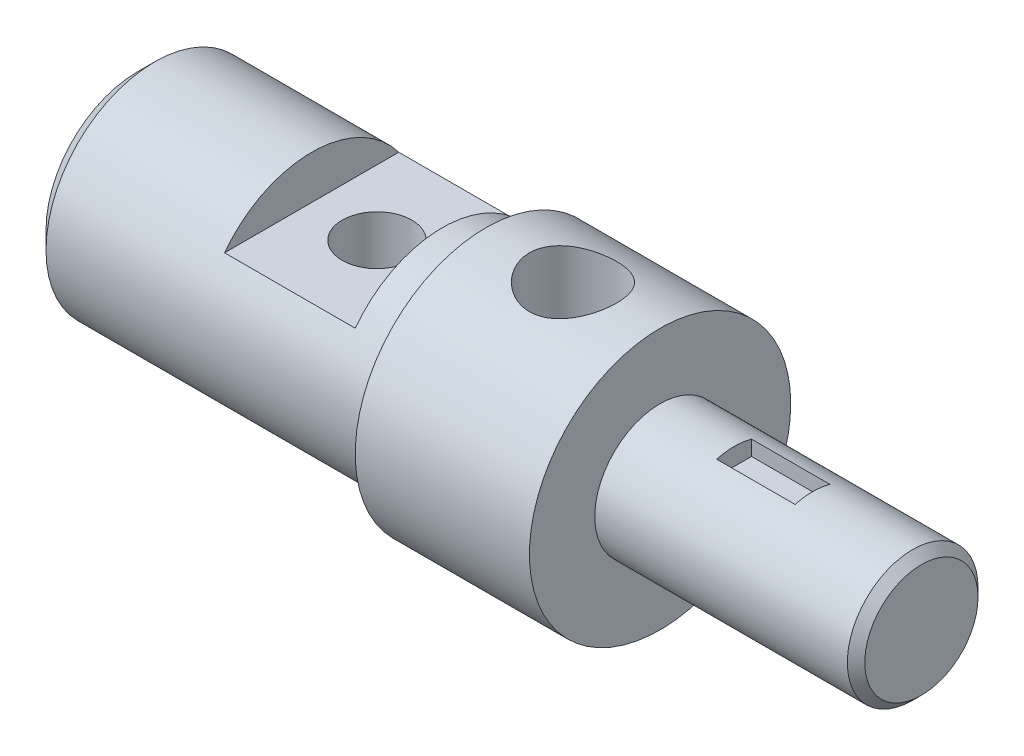
SolidWorks part; units mm, degrees
ref_plane "Спереди" through (0, 0, 0) normal (0, 0, 1) x (1, 0, 0)
ref_plane "Сверху" through (0, 0, 0) normal (0, 1, 0) x (1, 0, 0)
ref_plane "Справа" through (0, 0, 0) normal (1, 0, 0) x (0, 0, -1)
sketch "Эскиз1" plane through (0, 0, 0) normal (0, 0, 1) x (1, 0, 0)
  line L1 (0, 0) -> (0, 25)
  line L2 (0, 25) -> (80, 25)
  line L3 (80, 25) -> (80, 30)
  line L4 (80, 30) -> (120, 30)
  line L5 (120, 30) -> (120, 15)
  line L6 (120, 15) -> (180, 15)
  line L7 (180, 15) -> (180, 0)
  line L8 (0, 0) -> (180, 0)
  line L9 (0, 0) -> (-45.0163, 0) construction
  dimension "D1" = 60
  dimension "D2" = 50
  dimension "D3" = 30
  dimension "D4" = 180
  dimension "D5" = 80
  dimension "D6" = 60
revolve "Повернуть1" add sketch "Эскиз1" angle 360 about L9
sketch "Эскиз10" plane through (0, 0, 0) normal (0, 0, 1) x (1, 0, 0)
  line L0 (80, 25) -> (0, 25) construction
  line L1 (40, 25) -> (70, 25)
  line L2 (40, 25) -> (40, 15)
  line L3 (40, 15) -> (70, 15)
  line L4 (70, 25) -> (70, 15)
  line L5 (0, 25) -> (0, -25) construction
  line L6 (0, -25) -> (80, -25) construction
  dimension "D1" = 40
  dimension "D2" = 30
  dimension "D3" = 40
extrude "Вырез-Вытянуть7" cut sketch "Эскиз10" against normal through all both and the other way through all
ref_plane "Плоскость4" through (0, 30, 0) normal (0, 1, 0) x (1, 0, 0)
sketch "Эскиз14" plane through (0, 15, 0) normal (0, 1, 0) x (1, 0, 0)
  line L0 (40, 0) -> (70, 0) construction
  line L1 (40, -20) -> (40, 20) construction
  line L2 (70, 20) -> (70, -20) construction
  circle A0 centre (55, 0) radius 8
  point P9 (55, 0)
  dimension "D1" = 16
extrude "Вырез-Вытянуть8" cut sketch "Эскиз14" against normal through all
sketch "Эскиз6" plane through (0, 0, 0) normal (0, 0, 1) x (1, 0, 0)
  line L0 (180, 15) -> (120, 15) construction
  line L1 (137, 15) -> (155, 15)
  line L2 (137, 15) -> (137, 11)
  line L3 (137, 11) -> (155, 11)
  line L4 (155, 15) -> (155, 11)
  line L5 (180, -15) -> (180, 15) construction
  dimension "D1" = 18
  dimension "D2" = 25
  dimension "D3" = 4
extrude "Вырез-Вытянуть4" cut sketch "Эскиз6" against normal mid plane 8
ref_plane "Плоскость5" through (0, 30, 0) normal (0, 1, 0) x (1, 0, 0)
hole_wizard "Диаметр отверстия Ø20.0 (20)1" positions "Эскиз15" profile "Эскиз16" hole size "Ø20.0" standard "ISO"
sketch "Эскиз15" plane through (0, 30, 0) normal (0, 1, 0) x (1, 0, 0)
  line L0 (80, 30) -> (80, -30) construction
  point P0 (100, 0)
  dimension "D1" = 20
sketch "Эскиз16" plane through (100, 30, 0) normal (1, 0, 0) x (0, 0, 1)
  line L0 (0, 0) -> (0, 41.0086)
  line L1 (0, 41.0086) -> (10, 35)
  line L2 (10, 35) -> (10, 0)
  line L5 (10, 0) -> (0, 0)
  line L10 (0, 41.0086) -> (-10, 35) construction
  line L11 (0, -6.35) -> (0, 107.95) construction
  dimension "Диаметр отверстия" = 20
  dimension "Глубина отверстия" = 35
  dimension "Угол заточки сверла" = 118
chamfer "Фаска3" distance 2 angle 45 1 edges at (180, 0, -15)
chamfer "Фаска4" distance 4 angle 45 1 edges at (0, 0, -25)
